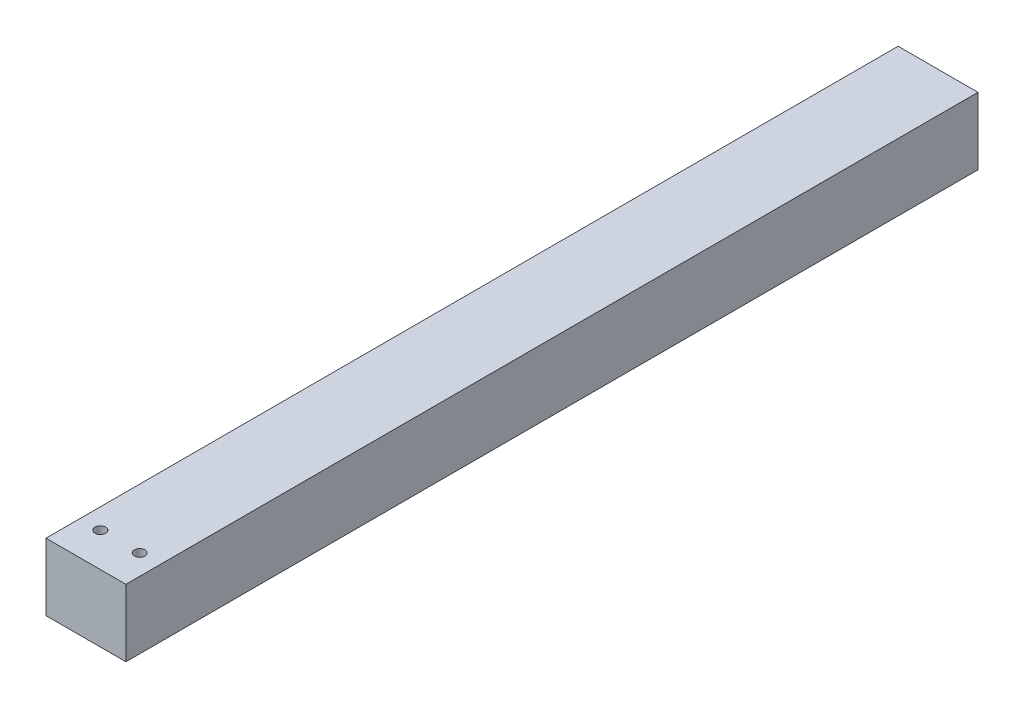
SolidWorks part; units mm, degrees
ref_plane "Front" through (0, 0, 0) normal (0, 0, 1) x (1, 0, 0)
ref_plane "Top" through (0, 0, 0) normal (0, 1, 0) x (1, 0, 0)
ref_plane "Right" through (0, 0, 0) normal (1, 0, 0) x (0, 0, -1)
sketch "Esquisse1" plane through (0, 0, 0) normal (0, 0, 1) x (1, 0, 0)
  line L1 (0, 0) -> (75, 0)
  line L2 (0, 0) -> (0, 63)
  line L3 (0, 63) -> (75, 63)
  line L4 (75, 0) -> (75, 63)
  dimension "D1" = 63
  dimension "D2" = 75
extrude "Boss.-Extru.1" add sketch "Esquisse1" along normal blind 800
sketch "Esquisse2" plane through (0, 0, 0) normal (0, -1, 0) x (1, 0, 0)
  line L0 (19, 800) -> (19, 952) construction
  line L1 (0, 800) -> (75, 800) construction
  line L2 (0, 800) -> (0, 0) construction
  line L3 (37.5, 800) -> (37.5, 952) construction
  circle A1 centre (19, 768) radius 5
  circle A2 centre (56, 768) radius 5
  point P4 (37.5, 952)
  point P13 (19, 985)
  dimension "D1" = 10
  dimension "D2" = 32
  dimension "D3" = 19
extrude "Enlèv. mat.-Extru.1" cut sketch "Esquisse2" against normal through all
